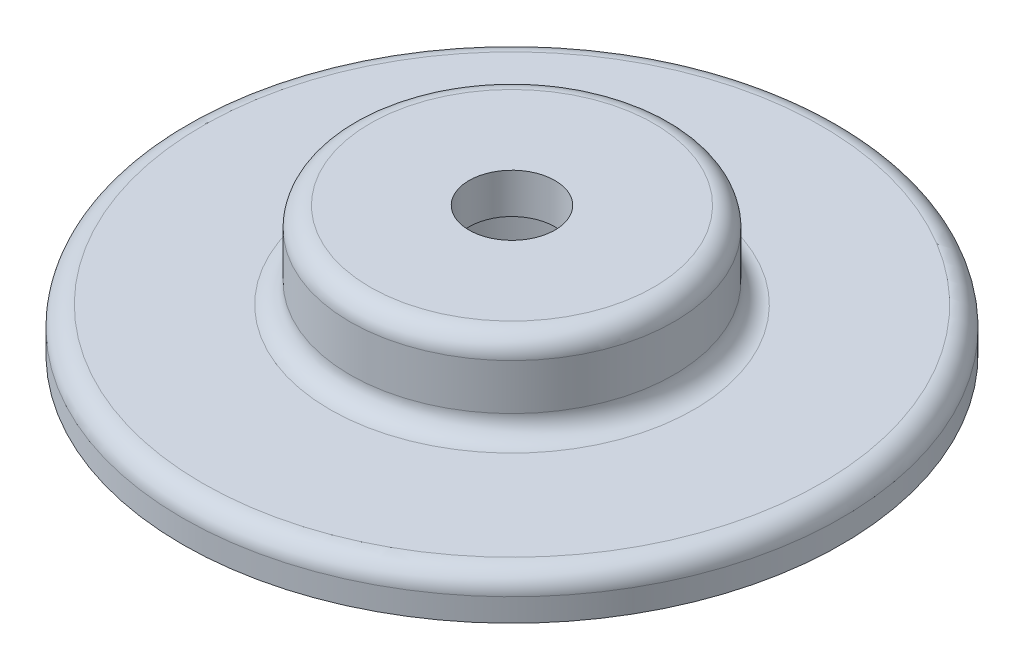
SolidWorks part; units mm, degrees
ref_plane "Front Plane" through (0, 0, 0) normal (0, 0, 1) x (1, 0, 0)
ref_plane "Top Plane" through (0, 0, 0) normal (0, 1, 0) x (1, 0, 0)
ref_plane "Right Plane" through (0, 0, 0) normal (1, 0, 0) x (0, 0, -1)
sketch "Sketch1" plane through (0, 0, 0) normal (0, 1, 0) x (1, 0, 0)
  circle A0 centre (0, 0) radius 11.5
  dimension "D1" = 23
extrude "Boss-Extrude1" add sketch "Sketch1" along normal blind 4.5
sketch "Sketch2" plane through (0, 0, 0) normal (0, -1, 0) x (1, 0, 0)
  circle A0 centre (0, 0) radius 3.65
  dimension "D1" = 7.3
extrude "Cut-Extrude1" cut sketch "Sketch2" against normal blind 3.1
sketch "Sketch3" plane through (0, 3.1, 0) normal (0, -1, 0) x (1, 0, 0)
  circle A0 centre (0, 0) radius 1.5
  dimension "D1" = 3
extrude "Cut-Extrude2" cut sketch "Sketch3" against normal through all
sketch "Sketch4" plane through (0, 4.5, 0) normal (0, 1, 0) x (1, 0, 0)
  circle A0 centre (0, 0) radius 3.65 construction
  circle A1 centre (0, 0) radius 5.65
  circle A2 centre (0, 0) radius 11.5 construction
  circle A3 centre (0, 0) radius 11.5
  dimension "D1" = 7.3
  dimension "D2" = 2
extrude "Cut-Extrude4" cut sketch "Sketch4" against normal blind 3
fillet "Fillet2" radius 0.7 3 edges at (0, 4.5, 5.65) (0, 1.5, 5.65) (0, 1.5, 11.5)
